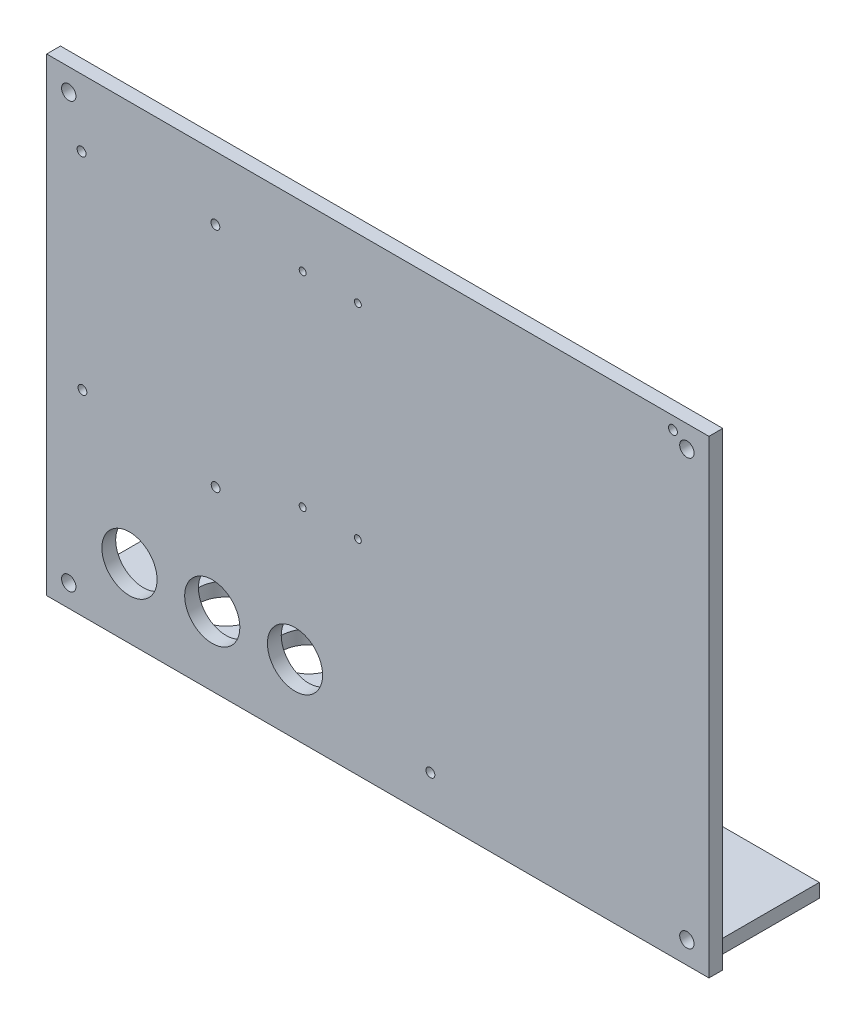
SolidWorks part; units mm, degrees
ref_plane "Plan de face" through (0, 0, 0) normal (0, 0, 1) x (1, 0, 0)
ref_plane "Plan de dessus" through (0, 0, 0) normal (0, 1, 0) x (1, 0, 0)
ref_plane "Plan de droite" through (0, 0, 0) normal (1, 0, 0) x (0, 0, -1)
sketch "Esquisse1" plane through (0, 0, 0) normal (0, 0, 1) x (1, 0, 0)
  line L0 (-71.7649, -103.8548) -> (-71.7649, 0) construction
  line L1 (-81.7649, 8.8453) -> (158.2351, 8.8453)
  line L2 (-81.7649, 8.8453) -> (-81.7649, -161.1547)
  line L3 (-81.7649, -161.1547) -> (158.2351, -161.1547)
  line L4 (158.2351, 8.8453) -> (158.2351, -161.1547)
  line L5 (-51.7973, 7.8453) -> (-63.7973, 7.8453) construction
  dimension "D1" = 10
  dimension "D2" = 1
  dimension "D3" = 170
  dimension "D4" = 240
extrude "Boss.-Extru.1" add sketch "Esquisse1" along normal blind 5
sketch "Esquisse2" plane through (0, 0, 0) normal (0, 0, -1) x (-1, 0, 0)
  circle A0 centre (-145.2, 4.3453) radius 1.6 construction
  circle A1 centre (-145.2, 4.3453) radius 1.6
  circle A2 centre (20.5387, -96.4658) radius 1.6 construction
  circle A3 centre (68.7987, -90.1158) radius 1.6 construction
  circle A4 centre (69.1287, -15.4309) radius 1.6078 construction
  circle A5 centre (20.6327, -14.1547) radius 1.6078 construction
  circle A6 centre (-31, -87) radius 1.25 construction
  circle A7 centre (-11, -87) radius 1.25 construction
  circle A8 centre (-31, -13) radius 1.25 construction
  circle A9 centre (-11, -13) radius 1.25 construction
  circle A10 centre (20.5387, -96.4658) radius 1.6
  circle A11 centre (68.7987, -90.1158) radius 1.6
  circle A12 centre (69.1287, -15.4309) radius 1.6078
  circle A13 centre (20.6327, -14.1547) radius 1.6078
  circle A14 centre (-31, -87) radius 1.25
  circle A15 centre (-11, -87) radius 1.25
  circle A16 centre (-31, -13) radius 1.25
  circle A17 centre (-11, -13) radius 1.25
  arc A18 (-55.7, -147.1547) -> (-58.9, -147.1547) centre (-57.3, -147.1547) ccw construction
  arc A19 (-55.7, -147.1547) -> (-58.9, -147.1547) centre (-57.3, -147.1547) ccw
  arc A20 (-58.9, -147.1547) -> (-57.2973, -145.5547) centre (-57.3, -147.1547) ccw
extrude "Enlèv. mat.-Extru.1" cut sketch "Esquisse2" against normal blind 5 contours A16 | A1 | A12 | A13 | A17 | A11 | A10 | A14 | A15 | A19 A20
sketch "Esquisse3" plane through (0, 0, 5) normal (0, 0, 1) x (1, 0, 0)
  circle A0 centre (57.3, -147.1547) radius 1.6
extrude "Enlèv. mat.-Extru.2" cut sketch "Esquisse3" against normal blind 5
sketch "Esquisse4" plane through (0, 0, 0) normal (0, 0, -1) x (-1, 0, 0)
  line L0 (81.7649, -161.1547) -> (-158.2351, -161.1547) construction
  line L1 (81.7649, 8.8453) -> (81.7649, -161.1547) construction
  line L2 (-158.2351, -161.1547) -> (-158.2351, 8.8453) construction
  line L3 (-158.2351, 8.8453) -> (81.7649, 8.8453) construction
  circle A0 centre (73.7649, -153.1547) radius 2.6
  circle A1 centre (-150.2351, -153.1547) radius 2.6
  circle A2 centre (-150.2351, 0.8453) radius 2.6
  circle A3 centre (73.7649, 0.8453) radius 2.6
  dimension "D1" = 8
  dimension "D2" = 5.2
  dimension "D3" = 8
  dimension "D4" = 5.2
  dimension "D5" = 8
  dimension "D6" = 8
  dimension "D7" = 5.2
  dimension "D8" = 8
  dimension "D9" = 8
  dimension "D10" = 8
  dimension "D11" = 5.2
  dimension "D12" = 8
extrude "Enlèv. mat.-Extru.3" cut sketch "Esquisse4" against normal blind 5
sketch "Esquisse6" plane through (0, 0, 0) normal (0, 0, -1) x (-1, 0, 0)
  line L0 (81.7649, -161.1547) -> (-158.2351, -161.1547) construction
  line L1 (-153.2351, -161.1547) -> (76.7649, -161.1547)
  line L2 (-153.2351, -161.1547) -> (-153.2351, -156.1547)
  line L3 (-153.2351, -156.1547) -> (76.7649, -156.1547)
  line L4 (76.7649, -161.1547) -> (76.7649, -156.1547)
  line L5 (-158.2351, -161.1547) -> (-158.2351, 8.8453) construction
  line L6 (81.7649, 8.8453) -> (81.7649, -161.1547) construction
  dimension "D1" = 5
  dimension "D2" = 5
  dimension "D3" = 5
  dimension "D4" = 5
extrude "Boss.-Extru.2" add sketch "Esquisse6" along normal up to surface (40 mm away)
sketch "Esquisse8" plane through (0, -161.1547, 0) normal (0, -1, 0) x (1, 0, 0)
  line L0 (-76.7649, -40) -> (-76.7649, 0) construction
  line L1 (153.2351, -40) -> (-76.7649, -40) construction
  circle A0 centre (-41.7649, -20) radius 10
  circle A1 centre (-11.7649, -20) radius 10
  circle A2 centre (18.2351, -20) radius 10
  dimension "D1" = 35
  dimension "D2" = 20
  dimension "D3" = 30
  dimension "D4" = 30
  dimension "D5" = 20
  dimension "D6" = 20
  dimension "D7" = 20
extrude "Enlèv. mat.-Extru.4" cut sketch "Esquisse8" against normal blind 5
sketch "Esquisse9" plane through (0, 0, 0) normal (0, 0, -1) x (-1, 0, 0)
  line L0 (81.7649, 8.8453) -> (81.7649, -161.1547) construction
  line L1 (81.7649, -161.1547) -> (76.7649, -161.1547) construction
  circle A0 centre (51.7649, -136.1547) radius 10
  circle A1 centre (21.7649, -136.1547) radius 10
  circle A2 centre (-8.2351, -136.1547) radius 10
  dimension "D1" = 20
  dimension "D2" = 20
  dimension "D3" = 20
  dimension "D4" = 30
  dimension "D5" = 30
  dimension "D6" = 30
  dimension "D7" = 25
extrude "Enlèv. mat.-Extru.5" cut sketch "Esquisse9" against normal blind 10
